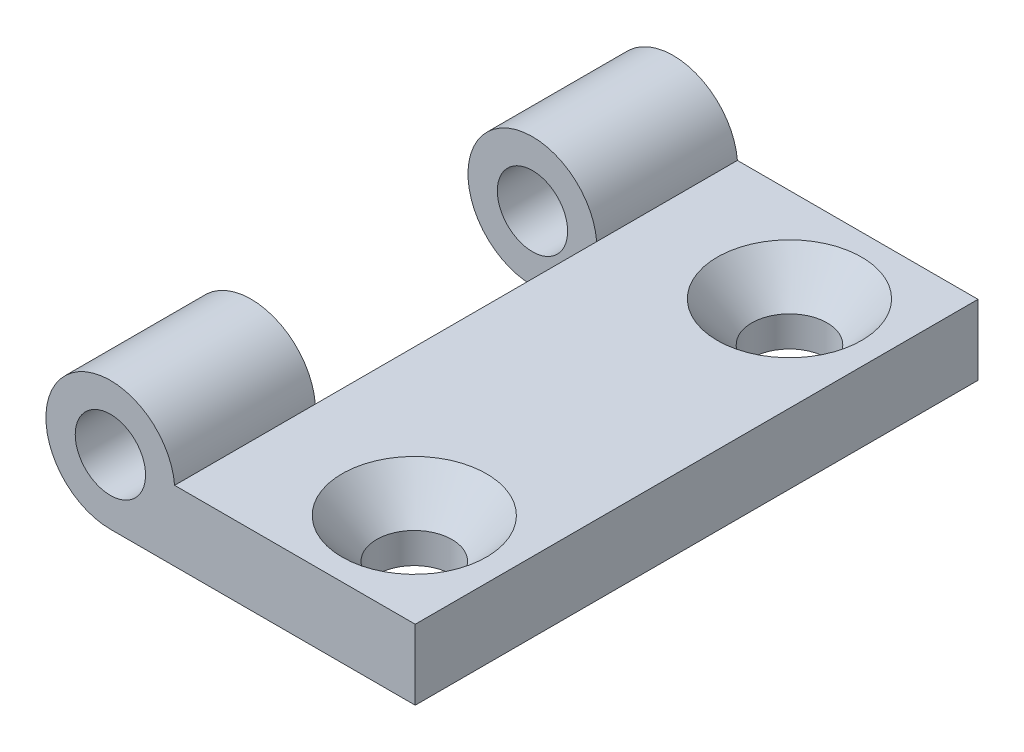
SolidWorks part; units mm, degrees
ref_plane "Front" through (0, 0, 0) normal (0, 0, 1) x (1, 0, 0)
ref_plane "Top" through (0, 0, 0) normal (0, 1, 0) x (1, 0, 0)
ref_plane "Right" through (0, 0, 0) normal (1, 0, 0) x (0, 0, -1)
sketch "Sketch1" plane through (0, 0, 0) normal (0, 0, 1) x (1, 0, 0)
  line L0 (4.3487, 4.7498) -> (20.6375, 4.7498)
  line L1 (20.6375, 0) -> (0, 0)
  line L4 (20.6375, 0) -> (20.6375, 4.7498)
  circle A0 centre (0, 4.3656) radius 2.3813
  arc A1 (4.3487, 4.7498) -> (-4.3487, 4.7498) centre (0, 4.3656) ccw
  arc A2 (0, 0) -> (-4.3487, 4.7498) centre (0, 4.3656) cw
  dimension "D1" = 8.7312
  dimension "D3" = 4.7625
  dimension "D5" = 4.3656
  dimension "D2" = 4.7498
  dimension "D4" = 20.6375
  dimension "D6" = 16.2888
extrude "Extrude1" add sketch "Sketch1" along normal mid plane 38.1
hole_wizard "CSK for #10 Flat Head Machine Screw1" positions "Sketch7" profile "Sketch6" countersink size "#10" standard "Ansi Inch" end condition through all
sketch "Sketch7" plane through (0, 4.7498, 0) normal (0, 1, 0) x (-1, 0, 0)
  point P2 (-14.224, 12.7)
  point P3 (-14.224, -12.7)
  dimension "D1" = 6.4135
  dimension "D2" = 25.4
  dimension "D3" = 6.35
sketch "Sketch6" plane through (14.224, 4.7498, 12.7) normal (1, 0, 0) x (0, 0, 1)
  line L0 (0, 0) -> (0, 4.7498)
  line L1 (0, 4.7498) -> (2.5527, 4.7498)
  line L2 (2.5527, 4.7498) -> (2.5527, 2.6882)
  line L3 (2.5527, 2.6882) -> (4.8895, 0)
  line L5 (4.8895, 0) -> (0, 0)
  line L6 (-2.5527, 2.6882) -> (-4.8895, 0) construction
  line L11 (0, -6.35) -> (0, 107.95) construction
  dimension "Thru Hole Dia." = 5.1054
  dimension "Thru Hole Depth" = 4.7498
  dimension "Near C'Sink Dia." = 9.779
  dimension "Near C'Sink Angle" = 82
ref_plane "Plane1" through (0, 0, -9.525) normal (0, 0, -1) x (-1, 0, 0)
sketch "Sketch8" plane through (0, 0, -9.525) normal (0, 0, -1) x (-1, 0, 0)
  arc A0 (-4.3487, 4.7498) -> (0, 0) centre (0, 4.3656) ccw
  arc A1 (-4.3487, 4.7498) -> (0, 0) centre (0, 4.3656) cw
  arc A2 (0, 0) -> (-4.3487, 4.7498) centre (0, 4.3656) ccw construction
  dimension "D1" = 4.3656
extrude "Cut-Extrude1" cut sketch "Sketch8" against normal blind 19.05
